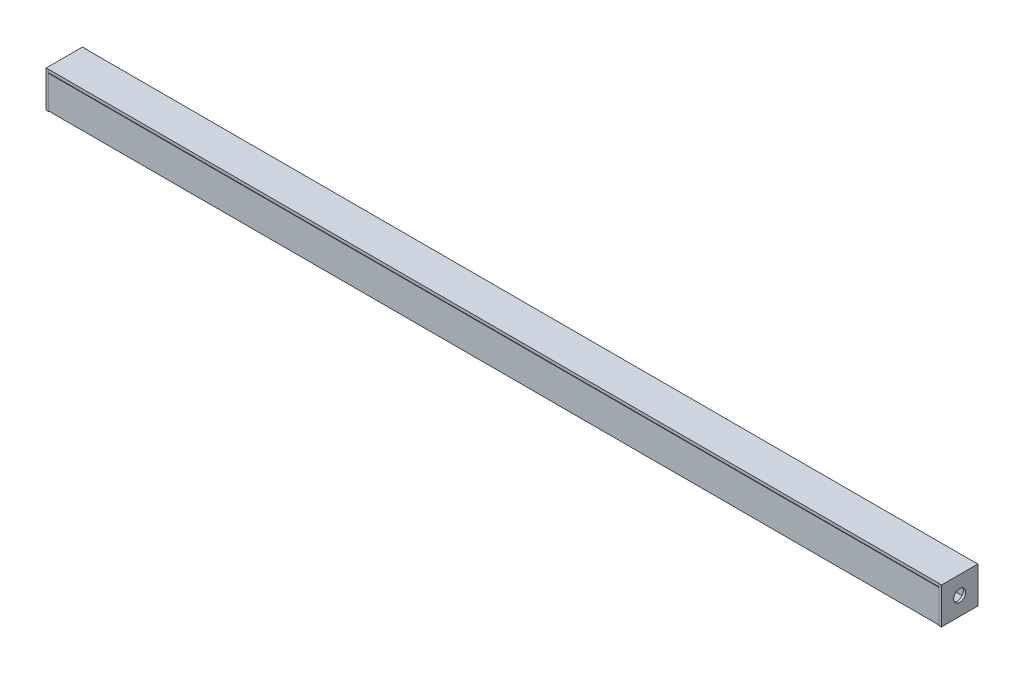
SolidWorks part; units mm, degrees
ref_plane "前视基准面" through (0, 0, 0) normal (0, 0, 1) x (1, 0, 0)
ref_plane "上视基准面" through (0, 0, 0) normal (0, 1, 0) x (1, 0, 0)
ref_plane "右视基准面" through (0, 0, 0) normal (1, 0, 0) x (0, 0, -1)
sketch "草图1" plane through (0, 0, 0) normal (1, 0, 0) x (0, 0, -1)
  line L1 (-24.2571, 16.9428) -> (-9.2571, 16.9428)
  line L2 (-24.2571, 16.9428) -> (-24.2571, 1.9428)
  line L3 (-24.2571, 1.9428) -> (-9.2571, 1.9428)
  line L4 (-9.2571, 16.9428) -> (-9.2571, 1.9428)
  line L5 (-24.2571, 16.9428) -> (-9.2571, 1.9428) construction
  line L6 (-24.2571, 1.9428) -> (-9.2571, 16.9428) construction
  point P4 (-16.7571, 9.4428)
  dimension "D1" = 15
  dimension "D2" = 15
extrude "凸台-拉伸1" add sketch "草图1" along normal blind 372
sketch "草图2" plane through (372, 0, 0) normal (1, 0, 0) x (0, 0, -1)
  line L0 (-24.2571, 16.9428) -> (-24.2571, 1.9428) construction
  line L1 (-24.2571, 15.6882) -> (-24.0571, 15.6882)
  line L2 (-24.2571, 15.6882) -> (-24.2571, 15.4882)
  line L3 (-24.2571, 15.4882) -> (-24.0571, 15.4882)
  line L4 (-24.0571, 15.6882) -> (-24.0571, 15.4882)
  line L5 (-24.2571, 15.6882) -> (-24.0571, 15.4882) construction
  line L6 (-24.2571, 15.4882) -> (-24.0571, 15.6882) construction
  line L7 (-9.2571, 1.9428) -> (-9.2571, 16.9428) construction
  line L8 (-9.2571, 15.6882) -> (-9.4571, 15.6882)
  line L9 (-9.2571, 15.6882) -> (-9.2571, 15.4882)
  line L10 (-9.2571, 15.4882) -> (-9.4571, 15.4882)
  line L11 (-9.4571, 15.6882) -> (-9.4571, 15.4882)
  line L12 (-9.2571, 15.6882) -> (-9.4571, 15.4882) construction
  line L13 (-9.2571, 15.4882) -> (-9.4571, 15.6882) construction
  circle A0 centre (-16.7571, 9.4428) radius 2.6
  point P6 (-24.1571, 15.5882)
  point P13 (-9.3571, 15.5882)
  point P16 (0, 0)
  dimension "D1" = 0.2
  dimension "D2" = 0.2
  dimension "D3" = 0.2
  dimension "D4" = 0.2
extrude "切除-拉伸2" cut sketch "草图2" against normal blind 372
sketch "草图3" plane through (0, 1.9428, 0) normal (0, -1, 0) x (1, 0, 0)
  line L0 (372, 24.2571) -> (0, 24.2571) construction
  line L1 (1, 23.2571) -> (371, 23.2571)
  line L2 (1, 23.2571) -> (1, 10.2571)
  line L3 (1, 10.2571) -> (371, 10.2571)
  line L4 (371, 23.2571) -> (371, 10.2571)
  line L5 (1, 23.2571) -> (371, 10.2571) construction
  line L6 (1, 10.2571) -> (371, 23.2571) construction
  line L7 (0, 24.2571) -> (0, 9.2571) construction
  line L8 (372, 9.2571) -> (0, 9.2571) construction
  line L9 (372, 24.2571) -> (372, 9.2571) construction
  point P4 (186, 16.7571)
  dimension "D1" = 1
  dimension "D2" = 1
  dimension "D3" = 1
  dimension "D4" = 1
extrude "切除-拉伸3" cut sketch "草图3" against normal blind 1
sketch "草图4" plane through (0, 0, 0) normal (-1, 0, 0) x (0, 0, 1)
  line L1 (9.2571, 16.9428) -> (24.2571, 16.9428)
  line L2 (9.2571, 16.9428) -> (9.2571, 1.9428)
  line L3 (9.2571, 1.9428) -> (24.2571, 1.9428)
  line L4 (24.2571, 16.9428) -> (24.2571, 1.9428)
  line L5 (9.2571, 16.9428) -> (24.2571, 1.9428) construction
  line L6 (9.2571, 1.9428) -> (24.2571, 16.9428) construction
  point P4 (16.7571, 9.4428)
extrude "切除-拉伸4" cut sketch "草图4" against normal blind 1
sketch "草图5" plane through (372, 0, 0) normal (1, 0, 0) x (0, 0, -1)
  line L1 (-24.2571, 16.9428) -> (-9.2571, 16.9428)
  line L2 (-24.2571, 16.9428) -> (-24.2571, 1.9428)
  line L3 (-24.2571, 1.9428) -> (-9.2571, 1.9428)
  line L4 (-9.2571, 16.9428) -> (-9.2571, 1.9428)
  line L5 (-24.2571, 16.9428) -> (-9.2571, 1.9428) construction
  line L6 (-24.2571, 1.9428) -> (-9.2571, 16.9428) construction
  point P4 (-16.7571, 9.4428)
extrude "切除-拉伸5" cut sketch "草图5" against normal blind 1
sketch "草图6" plane through (371, 0, 0) normal (1, 0, 0) x (0, 0, -1)
  line L0 (-24.2571, 15.4882) -> (-24.2571, 1.9428) construction
  line L1 (-23.0571, 14.9428) -> (-10.4571, 14.9428)
  line L2 (-23.0571, 14.9428) -> (-23.0571, 3.5438)
  line L3 (-23.0571, 3.5438) -> (-10.4571, 3.5438)
  line L4 (-10.4571, 14.9428) -> (-10.4571, 3.5438)
  line L5 (-23.0571, 14.9428) -> (-10.4571, 3.5438) construction
  line L6 (-23.0571, 3.5438) -> (-10.4571, 14.9428) construction
  line L7 (-9.2571, 1.9428) -> (-9.2571, 15.4882) construction
  line L8 (-9.2571, 16.9428) -> (-24.2571, 16.9428) construction
  point P4 (-16.7571, 9.2433)
  dimension "D1" = 1.2
  dimension "D2" = 1.2
  dimension "D3" = 2
extrude "切除-拉伸6" cut sketch "草图6" against normal blind 370
sketch "草图7" plane through (371, 0, 0) normal (1, 0, 0) x (0, 0, -1)
  line L0 (-24.2571, 16.9428) -> (-24.2571, 15.6882) construction
  line L1 (-24.3571, 16.9428) -> (-9.1571, 16.9428)
  line L2 (-24.3571, 16.9428) -> (-24.3571, 1.8428)
  line L3 (-24.3571, 1.8428) -> (-9.1571, 1.8428)
  line L4 (-9.1571, 16.9428) -> (-9.1571, 1.8428)
  line L5 (-24.3571, 16.9428) -> (-9.1571, 1.8428) construction
  line L6 (-24.3571, 1.8428) -> (-9.1571, 16.9428) construction
  line L7 (-9.2571, 16.9428) -> (-24.2571, 16.9428) construction
  line L8 (-9.2571, 1.9428) -> (-9.2571, 15.4882) construction
  line L9 (-10.2571, 1.9428) -> (-9.2571, 1.9428) construction
  circle A0 centre (-16.7571, 9.3928) radius 2.5
  point P4 (-16.7571, 9.3928)
  dimension "D1" = 0.1
  dimension "D2" = 0
  dimension "D3" = 0.1
  dimension "D4" = 0.1
extrude "凸台-拉伸4" add sketch "草图7" along normal blind 1
sketch "草图8" plane through (1, 0, 0) normal (-1, 0, 0) x (0, 0, 1)
  line L1 (9.1571, 16.9428) -> (24.3571, 16.9428)
  line L2 (9.1571, 16.9428) -> (9.1571, 1.8428)
  line L3 (9.1571, 1.8428) -> (24.3571, 1.8428)
  line L4 (24.3571, 16.9428) -> (24.3571, 1.8428)
  line L5 (9.1571, 16.9428) -> (24.3571, 1.8428) construction
  line L6 (9.1571, 1.8428) -> (24.3571, 16.9428) construction
  circle A0 centre (16.7571, 9.3928) radius 2.5
  point P4 (16.7571, 9.3928)
extrude "凸台-拉伸5" add sketch "草图8" along normal blind 1
